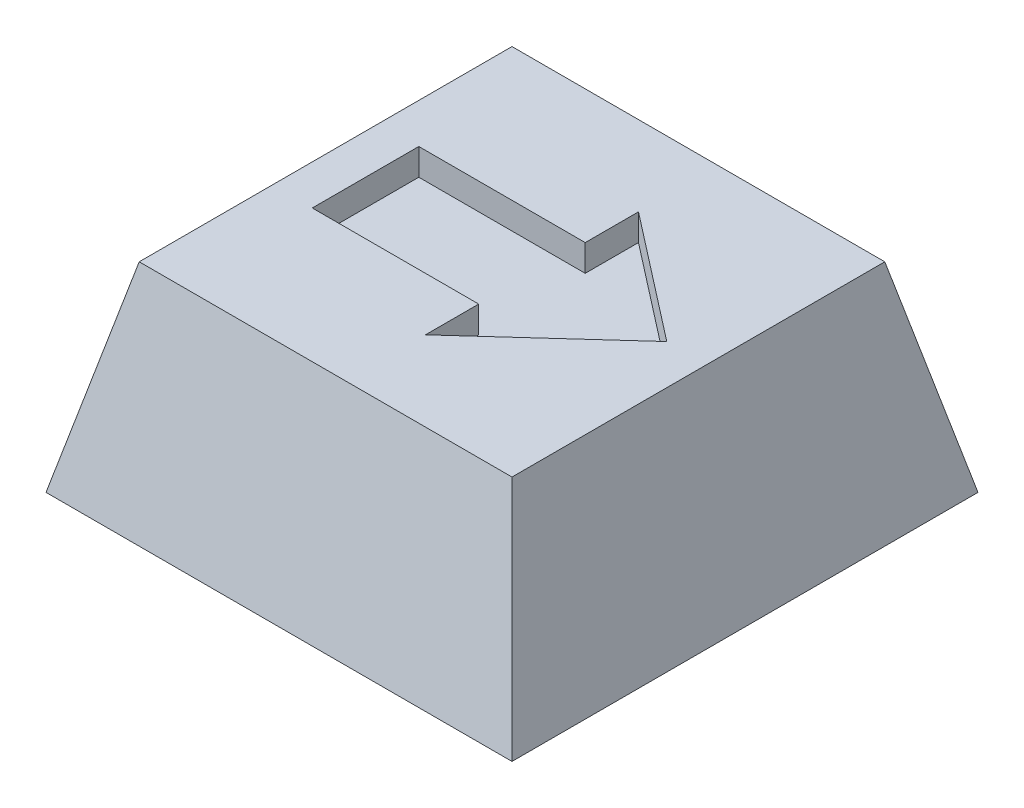
SolidWorks part; units mm, degrees
ref_plane "Front Plane" through (0, 0, 0) normal (0, 0, 1) x (1, 0, 0)
ref_plane "Top Plane" through (0, 0, 0) normal (0, 1, 0) x (1, 0, 0)
ref_plane "Right Plane" through (0, 0, 0) normal (1, 0, 0) x (0, 0, -1)
sketch "Sketch1" plane through (0, 0, 0) normal (0, 1, 0) x (1, 0, 0)
  line L1 (0, 0) -> (7, 0)
  line L2 (0, 0) -> (0, 7)
  line L3 (0, 7) -> (7, 7)
  line L4 (7, 0) -> (7, 7)
  dimension "D1" = 7
  dimension "D2" = 7
extrude "Boss-Extrude1" add sketch "Sketch1" along normal blind 3
sketch "Sketch2" plane through (0, 0, 0) normal (0, 0, 1) x (1, 0, 0)
  line L0 (0, 0) -> (0.7, 3)
  line L1 (0, 3) -> (7, 3) construction
  line L2 (0.7, 3) -> (0, 3)
  line L3 (0, 3) -> (0, 0)
  line L4 (7, 0) -> (6.3, 3)
  line L5 (6.3, 3) -> (7, 3)
  line L6 (7, 3) -> (7, 0)
  dimension "D1" = 0.7
  dimension "D2" = 0.7
extrude "Cut-Extrude1" cut sketch "Sketch2" against normal blind 7
sketch "Sketch3" plane through (0, 0, 0) normal (1, 0, 0) x (0, 0, -1)
  line L0 (0, 0) -> (0.7, 3)
  line L1 (7, 3) -> (0, 3) construction
  line L2 (0.7, 3) -> (0, 3)
  line L3 (0, 3) -> (0, 0)
  line L4 (7, 3) -> (6.3, 3)
  line L5 (6.3, 3) -> (7, 0)
  line L6 (7, 3) -> (7, 0)
  dimension "D1" = 0.7
  dimension "D2" = 0.7
extrude "Cut-Extrude2" cut sketch "Sketch3" along normal blind 11
sketch "Sketch4" plane through (0, 0, 0) normal (0, -1, 0) x (1, 0, 0)
  line L0 (3.5, 0) -> (3.5, -7) construction
  line L1 (0, 0) -> (7, 0) construction
  line L2 (7, -7) -> (0, -7) construction
  line L3 (0, -3.5) -> (7, -3.5) construction
  line L4 (0, -7) -> (0, 0) construction
  line L5 (7, 0) -> (7, -7) construction
  circle A0 centre (3.5, -3.5) radius 1.8
  dimension "D1" = 3.6
extrude "Cut-Extrude3" cut sketch "Sketch4" against normal blind 0.8
sketch "Sketch5" plane through (0, 3, 0) normal (0, 1, 0) x (1, 0, 0)
  line L0 (3.8, 4.3) -> (3.8, 5.1)
  line L1 (1.3, 4.3) -> (3.8, 4.3)
  line L2 (1.3, 4.3) -> (1.3, 2.7)
  line L3 (1.3, 2.7) -> (3.8, 2.7)
  line L4 (3.8, 4.3) -> (3.8, 2.7)
  line L5 (3.8, 5.1) -> (5.7, 3.6248)
  line L6 (5.7, 3.6248) -> (3.8, 1.9)
  line L7 (3.8, 1.9) -> (3.8, 2.7)
  line L8 (0.7, 6.3) -> (0.7, 0.7) construction
  line L9 (6.3, 6.3) -> (6.3, 0.7) construction
  line L10 (6.3, 6.3) -> (0.7, 6.3) construction
  line L11 (6.3, 0.7) -> (0.7, 0.7) construction
  dimension "D1" = 2.5
  dimension "D2" = 0.6
  dimension "D3" = 0.6
  dimension "D4" = 2
  dimension "D5" = 2
  dimension "D6" = 0.8
  dimension "D7" = 0.8
extrude "Cut-Extrude4" cut sketch "Sketch5" against normal blind 0.4 contours L4 L1 L2 L3 | L7 L6 L5 L0 L4
